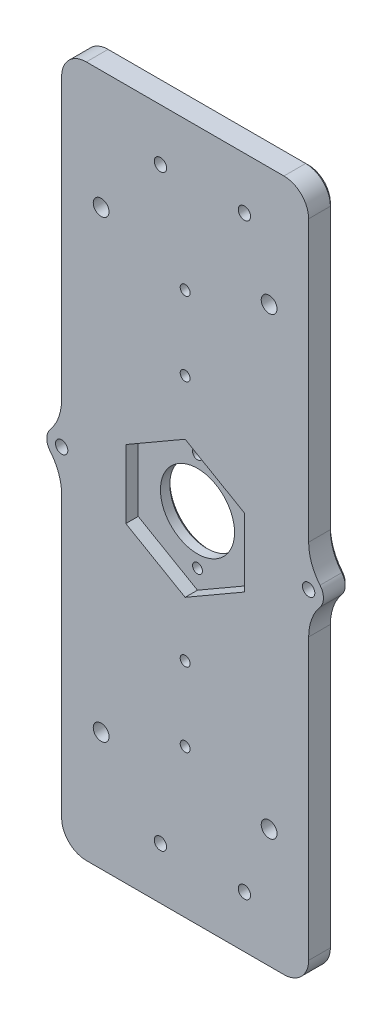
SolidWorks part; units mm, degrees
ref_plane "前视基准面" through (0, 0, 0) normal (0, 0, 1) x (1, 0, 0)
ref_plane "上视基准面" through (0, 0, 0) normal (0, 1, 0) x (1, 0, 0)
ref_plane "右视基准面" through (0, 0, 0) normal (1, 0, 0) x (0, 0, -1)
sketch "草图1" plane through (0, 0, 0) normal (0, 0, 1) x (1, 0, 0)
  line L0 (-43.0887, 0) -> (41.041, 0) construction
  line L2 (-25, -70) -> (25, -70)
  line L3 (-25, -70) -> (-25, 70)
  line L4 (-25, 70) -> (25, 70)
  line L5 (25, -70) -> (25, 70)
  line L6 (-25, -70) -> (25, 70) construction
  line L7 (-25, 70) -> (25, -70) construction
  point P1 (0, 0)
  dimension "D1" = 50
  dimension "D2" = 140
extrude "凸台-拉伸1" add sketch "草图1" along normal blind 5
ref_plane "基准面4" through (0, 0, 0) normal (0, 1, 0) x (1, 0, 0)
sketch "草图16" plane through (0, 0, 5) normal (0, 0, 1) x (1, 0, 0)
  line L0 (25, -70) -> (25, 70) construction
  line L1 (0, 12.5235) -> (0, -16.2563) construction
  circle A0 centre (25, 0) radius 3
  circle A1 centre (-25, 0) radius 3
  dimension "D1" = 6
extrude "凸台-拉伸2" add sketch "草图16" against normal up to surface (5 mm away) up to face at (0, 0, 0)
sketch "草图11" plane through (0, 0, 5) normal (0, 0, 1) x (1, 0, 0)
  line L1 (0, 13.8564) -> (-12, 6.9282)
  line L2 (-12, 6.9282) -> (-12, -6.9282)
  line L3 (-12, -6.9282) -> (0, -13.8564)
  line L4 (0, -13.8564) -> (12, -6.9282)
  line L5 (12, -6.9282) -> (12, 6.9282)
  line L6 (12, 6.9282) -> (0, 13.8564)
  circle A0 centre (0, 0) radius 12 construction
  dimension "D1" = 24
extrude "切除-拉伸5" cut sketch "草图11" against normal blind 2.5
sketch "草图12" plane through (0, 0, 2.5) normal (0, 0, 1) x (1, 0, 0)
  circle A0 centre (0, 0) radius 7.5
  dimension "D1" = 15
extrude "切除-拉伸6" cut sketch "草图12" against normal blind 2.5
sketch "草图13" plane through (0, 0, 5) normal (0, 0, 1) x (1, 0, 0)
  line L0 (0, 59.2164) -> (0, -84.7055) construction
  line L2 (0, 0) -> (35.6711, 0) construction
  circle A0 centre (25, 0) radius 1.25
  circle A1 centre (-25, 0) radius 1.25
  dimension "D1" = 2.5
  dimension "D2" = 25
extrude "切除-拉伸7" cut sketch "草图13" against normal through all
fillet "圆角2" radius 10 4 edges at (-25, 3, 2.5) (-25, -3, 2.5) (25, -3, 2.5) (25, 3, 2.5)
fillet "圆角1" radius 5 4 edges at (-25, 70, 2.5) (-25, -70, 2.5) (25, -70, 2.5) (25, 70, 2.5)
sketch "草图14" plane through (0, 0, 5) normal (0, 0, 1) x (1, 0, 0)
  line L0 (-46.3377, 0) -> (49.3744, 0) construction
  line L1 (0, 65.2326) -> (0, -64.7827) construction
  line L2 (20, 70) -> (-20, 70) construction
  line L3 (-5, 59.5) -> (12, 59.5) construction
  circle A0 centre (0, 10) radius 1
  circle A1 centre (0, 25) radius 1
  circle A2 centre (0, 40) radius 1
  circle A3 centre (17, 46) radius 1.6
  circle A4 centre (-17, 46) radius 1.6
  circle A5 centre (-5, 59.5) radius 1.25
  circle A6 centre (12, 59.5) radius 1.25
  dimension "D1" = 2
  dimension "D2" = 10
  dimension "D4" = 24
  dimension "D5" = 34
  dimension "D6" = 3.2
  dimension "D7" = 2.5
  dimension "D8" = 2.5
  dimension "D9" = 5
  dimension "D10" = 12
  dimension "D11" = 13.5
  dimension "D3" = 3
extrude "切除-拉伸8" cut sketch "草图14" against normal through all
mirror "镜向1" about plane through (0, 0, 0) normal (0, 1, 0) of "切除-拉伸8"
chamfer "倒角1" distance 0.6 angle 45 33 edges at (-23.5355, -68.5355, 0) (0, -70, 0) (23.5355, -68.5355, 0) (25, 36.6533, 0) (25, -36.6533, 0) (23.5355, 68.5355, 0) (0, 70, 0) (-23.5355, 68.5355, 0) (-25, 36.6533, 0) (-25, -36.6533, 0) (7.5, 0, 0) (-26.25, 0, 0) (26.25, 0, 0) (13.25, 59.5, 0) (-3.75, 59.5, 0) (18.6, 46, 0) (1, 25, 0) (1, 40, 0) (-18.6, 46, 0) (1, 10, 0) (13.25, -59.5, 0) (-3.75, -59.5, 0) (18.6, -46, 0) (1, -25, 0) (1, -40, 0) (-18.6, -46, 0) (1, -10, 0) (-25.5946, 4.9098, 0) (-28, 0, 0) (-25.5946, -4.9098, 0) (25.5946, -4.9098, 0) (28, 0, 0) (25.5946, 4.9098, 0)
